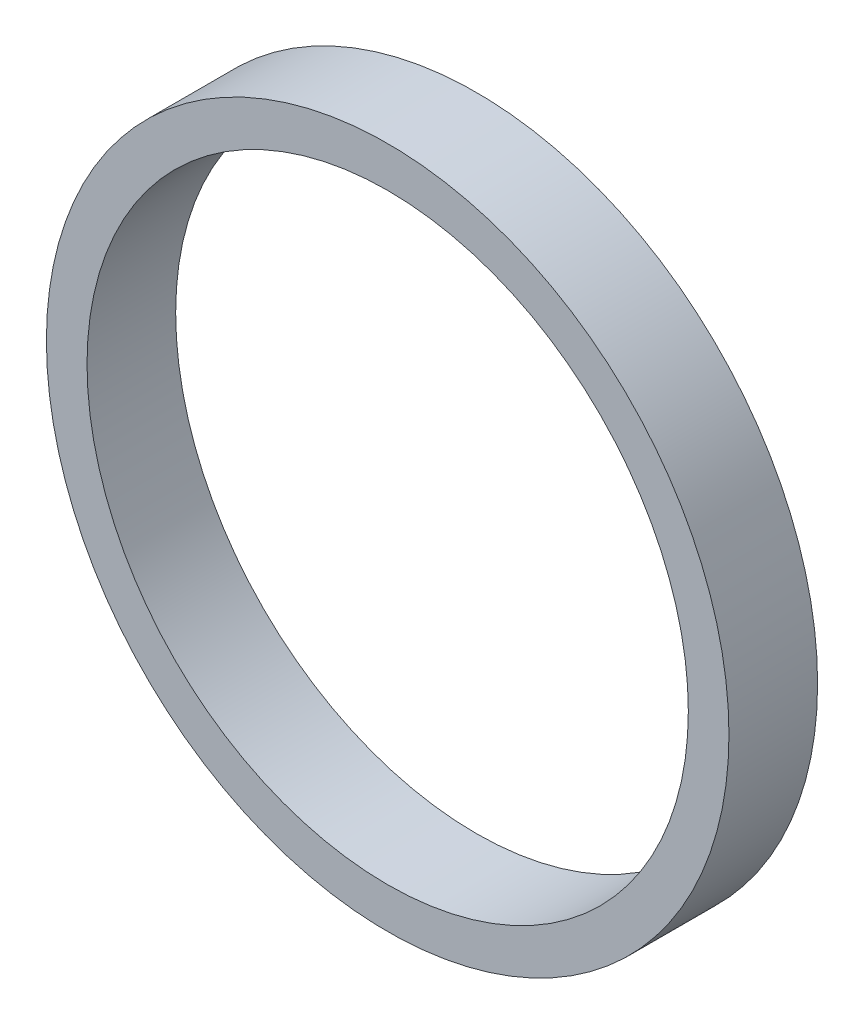
SolidWorks part; units mm, degrees
material "ABS"
ref_plane "Front Plane" through (0, 0, 0) normal (0, 0, 1) x (1, 0, 0)
ref_plane "Top Plane" through (0, 0, 0) normal (0, 1, 0) x (1, 0, 0)
ref_plane "Right Plane" through (0, 0, 0) normal (1, 0, 0) x (0, 0, -1)
sketch "Sketch1" plane through (0, 0, 0) normal (0, 0, 1) x (1, 0, 0)
  circle A0 centre (0, 0) radius 5.0875
  circle A1 centre (0, 0) radius 5.775
  dimension "D1" = 10.175
  dimension "D2" = 11.55
extrude "Boss-Extrude1" add sketch "Sketch1" along normal blind 1.5
equation "\"RingPinShaft\"= 5.05"
equation "\"CenterBearingOut\"=32.00"
equation "\"RingPostIn\"=5.15"
equation "\"CamBearingOut\"=15.1"
equation "\"DiskOutputShaft\"=10.1"
equation "\"CenterShaft\"=25.2"
equation "\"Eccentricity\"=2"
equation "\"CycCamShaft\"=10.05"
equation "\"D1@Sketch1\"=\"CycCamShaft\" + 0.125"
equation "\"D2@Sketch1\"=\"CycCamShaft\"+1.5"
